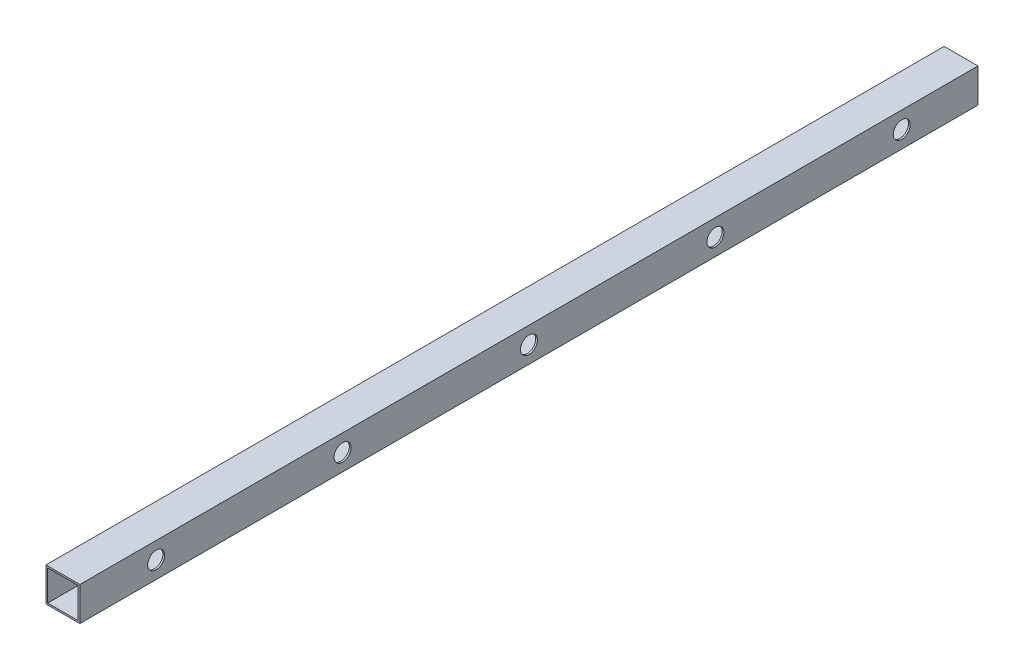
SolidWorks part; units mm, degrees
material "1060-H12"
ref_plane "Alzado" through (0, 0, 0) normal (0, 0, 1) x (1, 0, 0)
ref_plane "Planta" through (0, 0, 0) normal (0, 1, 0) x (1, 0, 0)
ref_plane "Vista lateral" through (0, 0, 0) normal (1, 0, 0) x (0, 0, -1)
sketch "Croquis1" plane through (0, 0, 0) normal (0, 0, 1) x (1, 0, 0)
  line L1 (20, -20) -> (-20, -20)
  line L2 (20, -20) -> (20, 20)
  line L3 (20, 20) -> (-20, 20)
  line L4 (-20, -20) -> (-20, 20)
  line L5 (20, -20) -> (-20, 20) construction
  line L6 (20, 20) -> (-20, -20) construction
  point P0 (0, 0)
  dimension "D1" = 40
  dimension "D2" = 40
extrude "Extruir-Lámina1" add sketch "Croquis1" along normal blind 1060 thin
sketch "Croquis2" plane through (20, 0, 0) normal (1, 0, 0) x (0, 0, -1)
  line L0 (-1060, 0) -> (0, 0) construction
  line L1 (-1060, -20) -> (-1060, 20) construction
  line L2 (-530, 0) -> (-530, 140.1979) construction
  circle A0 centre (-530, 0) radius 10
  circle A1 centre (-310, 0) radius 10
  circle A2 centre (-90, 0) radius 10
  circle A3 centre (-750, 0) radius 10
  circle A4 centre (-970, 0) radius 10
  dimension "D1" = 20
extrude "Extruir1" cut sketch "Croquis2" against normal blind 10
